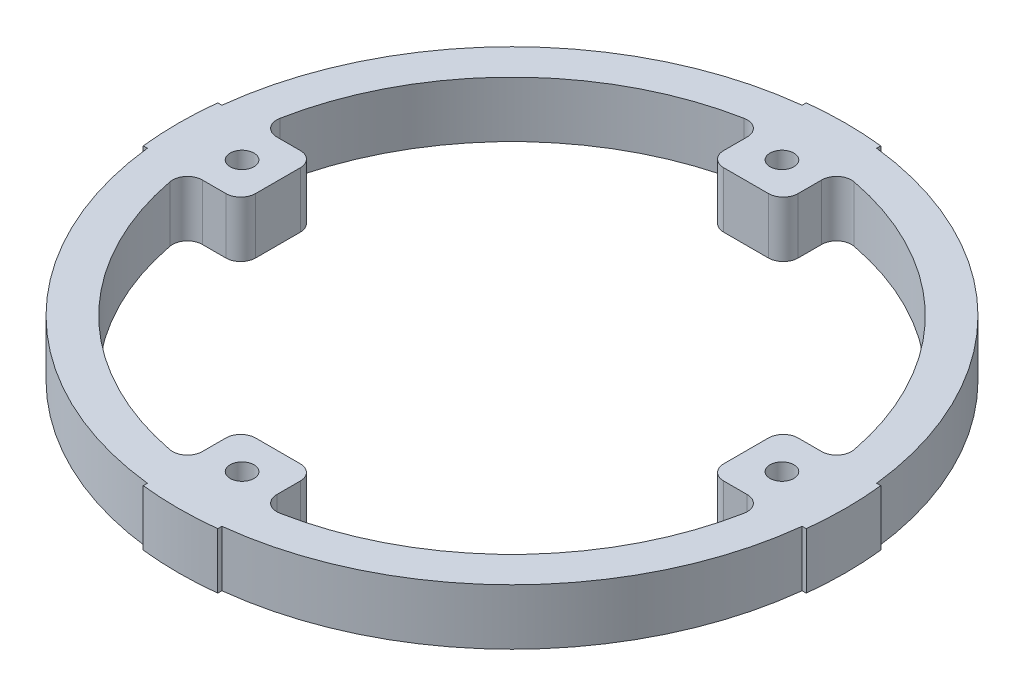
SolidWorks part; units mm, degrees
ref_plane "Front Plane" through (0, 0, 0) normal (0, 0, 1) x (1, 0, 0)
ref_plane "Top Plane" through (0, 0, 0) normal (0, 1, 0) x (1, 0, 0)
ref_plane "Right Plane" through (0, 0, 0) normal (1, 0, 0) x (0, 0, -1)
sketch "Sketch1" plane through (0, 0, 0) normal (0, 1, 0) x (1, 0, 0)
  line L0 (0, 0) -> (44.25, 0) construction
  line L1 (33.4302, 5) -> (36.5864, 5)
  line L2 (33.4302, -5) -> (36.5864, -5)
  line L3 (31.4302, 3) -> (31.4302, -3)
  line L7 (5, -33.4302) -> (5, -36.5864)
  line L8 (3, -31.4302) -> (-3, -31.4302)
  line L9 (-5, -33.4302) -> (-5, -36.5864)
  line L13 (-33.4302, -5) -> (-36.5864, -5)
  line L14 (-31.4302, -3) -> (-31.4302, 3)
  line L15 (-33.4302, 5) -> (-36.5864, 5)
  line L19 (-5, 33.4302) -> (-5, 36.5864)
  line L20 (-3, 31.4302) -> (3, 31.4302)
  line L21 (5, 33.4302) -> (5, 36.5864)
  line L25 (-5, 38.9302) -> (-5, 46.441) construction
  line L26 (5, 38.9302) -> (5, 47.4442) construction
  line L27 (-5, 43.9666) -> (-5, 44.5201)
  line L28 (5, 43.9666) -> (5, 44.5201)
  line L29 (43.9666, -5) -> (44.5201, -5)
  line L30 (43.9666, 5) -> (44.5201, 5)
  line L31 (-5, -43.9666) -> (-5, -44.5201)
  line L32 (5, -43.9666) -> (5, -44.5201)
  line L33 (-43.9666, 5) -> (-44.5201, 5)
  line L34 (-43.9666, -5) -> (-44.5201, -5)
  line L35 (-25.7601, 18.689) -> (-18.689, 25.7601) [skipped]
  line L36 (-25.7601, 18.689) -> (-31.0634, 23.9923) [skipped]
  line L37 (-18.689, 25.7601) -> (-23.9923, 31.0634) [skipped]
  line L38 (25.7601, -18.689) -> (31.0634, -23.9923) [skipped]
  line L39 (25.7601, -18.689) -> (18.689, -25.7601) [skipped]
  line L40 (18.689, -25.7601) -> (23.9923, -31.0634) [skipped]
  line L41 (-20.1032, -24.3458) -> (-24.3458, -20.1032) [skipped]
  line L42 (-27.1743, -20.1032) -> (-29.406, -22.3349) [skipped]
  line L43 (-20.1032, -27.1743) -> (-22.3349, -29.406) [skipped]
  line L44 (20.1032, 24.3458) -> (24.3458, 20.1032) [skipped]
  line L45 (20.1032, 27.1743) -> (22.3349, 29.406) [skipped]
  line L46 (27.1743, 20.1032) -> (29.406, 22.3349) [skipped]
  arc A0 (-43.9666, -5) -> (-5, -43.9666) centre (0, 0) ccw
  circle A1 centre (0, 0) radius 36.25 construction
  circle A2 centre (36.25, 0) radius 1.6
  arc A3 (38.5507, 7.3758) -> (32.475, 22.044) centre (0, 0) ccw
  arc A4 (-36.5864, 5) -> (-38.5507, 7.3758) centre (-36.5864, 7) cw
  circle A5 centre (0, -36.25) radius 1.6
  circle A7 centre (-36.25, 0) radius 1.6
  arc A8 (-36.5864, -5) -> (-38.5507, -7.3758) centre (-36.5864, -7) ccw
  circle A9 centre (0, 36.25) radius 1.6
  arc A11 (-7.3758, 38.5507) -> (-38.5507, 7.3758) centre (0, 0) ccw
  arc A12 (32.475, 22.044) -> (7.3758, 38.5507) centre (0, 0) ccw
  arc A14 (-38.5507, -7.3758) -> (-22.044, -32.475) centre (0, 0) ccw
  arc A15 (-22.044, -32.475) -> (-7.3758, -38.5507) centre (0, 0) ccw
  arc A16 (7.3758, -38.5507) -> (38.5507, -7.3758) centre (0, 0) ccw
  arc A18 (-44.5201, 5) -> (-44.5201, -5) centre (0, 0) ccw
  arc A19 (-5, -44.5201) -> (5, -44.5201) centre (0, 0) ccw
  arc A20 (-5, 43.9666) -> (-43.9666, 5) centre (0, 0) ccw
  arc A21 (5, 44.5201) -> (-5, 44.5201) centre (0, 0) ccw
  arc A22 (43.9666, 5) -> (5, 43.9666) centre (0, 0) ccw
  arc A23 (44.5201, -5) -> (44.5201, 5) centre (0, 0) ccw
  arc A24 (5, -43.9666) -> (43.9666, -5) centre (0, 0) ccw
  circle A25 centre (-25.6326, 25.6326) radius 1.6 [skipped]
  circle A26 centre (25.6326, -25.6326) radius 1.6 [skipped]
  arc A27 (-5, -36.5864) -> (-7.3758, -38.5507) centre (-7, -36.5864) cw
  arc A28 (5, -36.5864) -> (7.3758, -38.5507) centre (7, -36.5864) ccw
  arc A29 (36.5864, -5) -> (38.5507, -7.3758) centre (36.5864, -7) cw
  arc A30 (36.5864, 5) -> (38.5507, 7.3758) centre (36.5864, 7) ccw
  arc A33 (5, 36.5864) -> (7.3758, 38.5507) centre (7, 36.5864) cw
  arc A34 (-5, 36.5864) -> (-7.3758, 38.5507) centre (-7, 36.5864) ccw
  arc A35 (-5, 33.4302) -> (-3, 31.4302) centre (-3, 33.4302) ccw
  arc A36 (3, 31.4302) -> (5, 33.4302) centre (3, 33.4302) ccw
  arc A39 (33.4302, 5) -> (31.4302, 3) centre (33.4302, 3) ccw
  arc A40 (33.4302, -5) -> (31.4302, -3) centre (33.4302, -3) cw
  arc A41 (5, -33.4302) -> (3, -31.4302) centre (3, -33.4302) ccw
  arc A42 (-3, -31.4302) -> (-5, -33.4302) centre (-3, -33.4302) ccw
  arc A45 (-33.4302, -5) -> (-31.4302, -3) centre (-33.4302, -3) ccw
  arc A46 (-31.4302, 3) -> (-33.4302, 5) centre (-33.4302, 3) ccw
  circle A47 centre (-25.6326, -25.6326) radius 1.6 [skipped]
  circle A48 centre (25.6326, 25.6326) radius 1.6 [skipped]
  point P55 (0, 0)
  point P61 (38.9302, -5)
  point P76 (0, 0)
  point P93 (38.9302, 5)
  point P114 (31.4302, 5)
  point P117 (31.4302, -5)
  dimension "D1" = 88.5
  dimension "D2" = 72.5
  dimension "D3" = 3.2
  dimension "D4" = 5
  dimension "D8" = 89.6
  dimension "D10" = 2
  dimension "D11" = 2
  dimension "D5" = 7.5
  dimension "D6" = 10
  dimension "D7" = 8
  dimension "D9" = 4
extrude "Boss-Extrude1" add sketch "Sketch1" along normal blind 7.5
